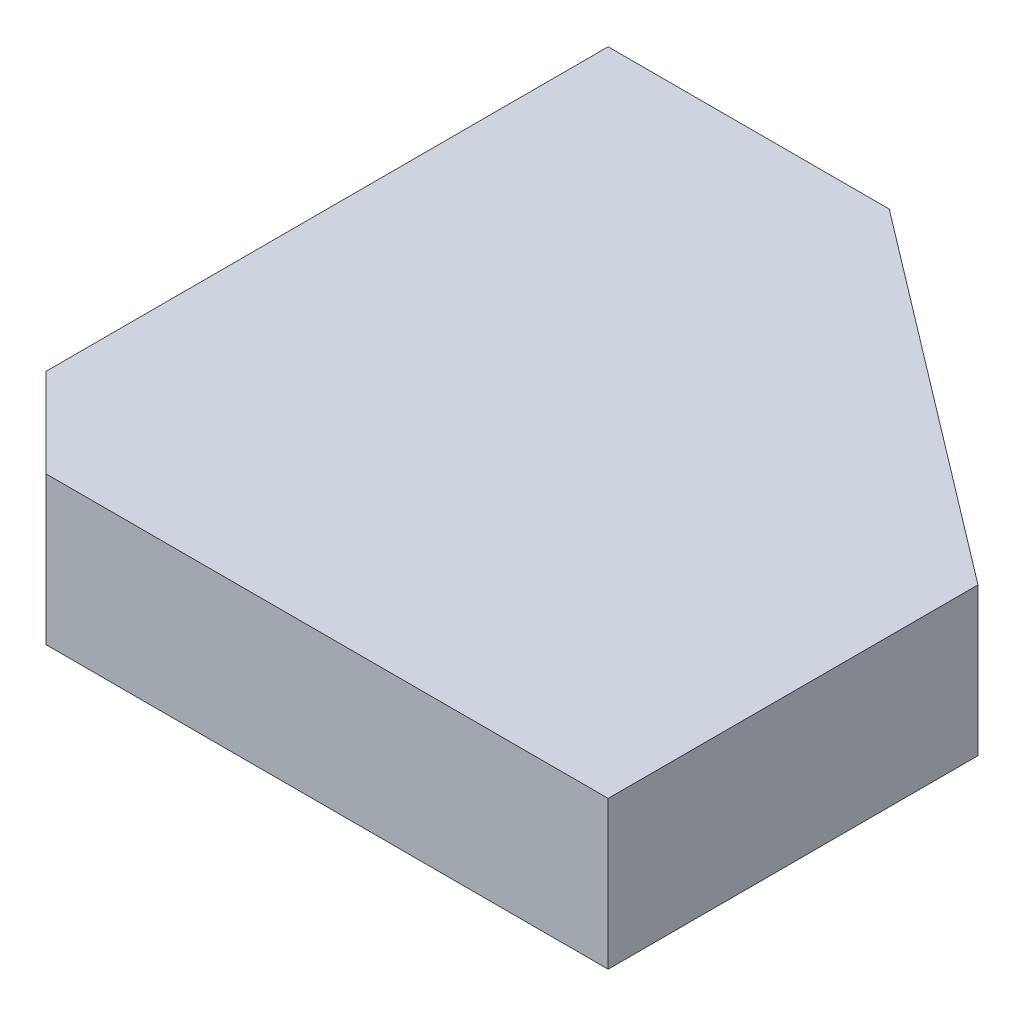
SolidWorks part; units mm, degrees
material "PW20:29:Sc:0:"
ref_plane "Front" through (0, 0, 0) normal (0, 0, 1) x (1, 0, 0)
ref_plane "Top" through (0, 0, 0) normal (0, 1, 0) x (1, 0, 0)
ref_plane "Right" through (0, 0, 0) normal (1, 0, 0) x (0, 0, -1)
sketch "Sketch1" plane through (0, 0, 0) normal (0, 1, 0) x (1, 0, 0)
  line L0 (0, 0) -> (44, 0)
  line L1 (0, 0) -> (0, 44)
  line L2 (19, 44) -> (0, 44)
  line L3 (44, 25) -> (44, 0)
  line L4 (19, 44) -> (44, 25)
  dimension "D1" = 44
  dimension "D2" = 44
  dimension "D3" = 25
  dimension "D4" = 19
extrude "Base-Extrude" add sketch "Sketch1" along normal mid plane 10
chamfer "Chamfer1" distance 6 angle 45 1 edges at (0, 0, 0)
